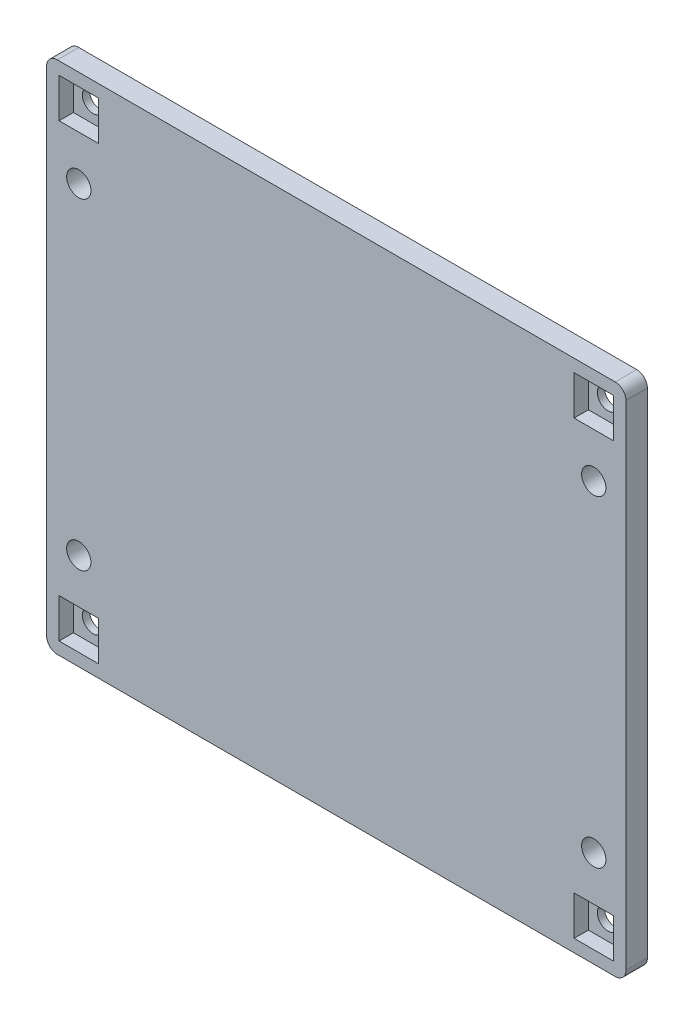
SolidWorks part; units mm, degrees
ref_plane "Alzado" through (0, 0, 0) normal (0, 0, 1) x (1, 0, 0)
ref_plane "Planta" through (0, 0, 0) normal (0, 1, 0) x (1, 0, 0)
ref_plane "Vista lateral" through (0, 0, 0) normal (1, 0, 0) x (0, 0, -1)
sketch "Model" plane through (0, 0, 0) normal (0, 0, 1) x (1, 0, 0)
  line L0 (85.4827, 227.2463) -> (7.4781, 227.2463)
  line L1 (5.9781, 228.7463) -> (5.9781, 297.7487)
  line L2 (7.4781, 299.2487) -> (85.4827, 299.2487)
  line L3 (86.9827, 297.7487) -> (86.9827, 228.7463)
  circle A0 centre (82.483, 294.7487) radius 1.5
  circle A1 centre (10.4781, 231.7459) radius 1.5
  circle A2 centre (82.483, 231.7459) radius 1.5
  circle A3 centre (10.4781, 294.7487) radius 1.5
  circle A4 centre (10.4781, 240.7456) radius 1.7
  circle A5 centre (10.4781, 285.749) radius 1.7
  circle A6 centre (82.483, 240.7456) radius 1.7
  circle A7 centre (82.483, 285.749) radius 1.7
  arc A8 (7.4781, 299.2487) -> (5.9781, 297.7487) centre (7.4781, 297.7487) ccw
  arc A9 (86.9827, 297.7487) -> (85.4827, 299.2487) centre (85.4827, 297.7487) ccw
  arc A10 (85.4827, 227.2463) -> (86.9827, 228.7463) centre (85.4827, 228.7463) ccw
  arc A11 (5.9781, 228.7463) -> (7.4781, 227.2463) centre (7.4781, 228.7463) ccw
extrude "Saliente-Extruir1" add sketch "Model" along normal blind 3
sketch "Croquis2" plane through (0, 0, 3) normal (0, 0, 1) x (1, 0, 0)
  line L1 (7.7281, 297.4987) -> (13.2281, 297.4987)
  line L2 (7.7281, 297.4987) -> (7.7281, 291.9987)
  line L3 (7.7281, 291.9987) -> (13.2281, 291.9987)
  line L4 (13.2281, 297.4987) -> (13.2281, 291.9987)
  line L5 (7.7281, 297.4987) -> (13.2281, 291.9987) construction
  line L6 (7.7281, 291.9987) -> (13.2281, 297.4987) construction
  line L7 (85.233, 297.4987) -> (79.733, 297.4987)
  line L8 (85.233, 297.4987) -> (85.233, 291.9987)
  line L9 (85.233, 291.9987) -> (79.733, 291.9987)
  line L10 (79.733, 297.4987) -> (79.733, 291.9987)
  line L11 (85.233, 297.4987) -> (79.733, 291.9987) construction
  line L12 (85.233, 291.9987) -> (79.733, 297.4987) construction
  line L13 (13.2281, 234.4959) -> (7.7281, 234.4959)
  line L14 (13.2281, 234.4959) -> (13.2281, 228.9959)
  line L15 (13.2281, 228.9959) -> (7.7281, 228.9959)
  line L16 (7.7281, 234.4959) -> (7.7281, 228.9959)
  line L17 (13.2281, 234.4959) -> (7.7281, 228.9959) construction
  line L18 (13.2281, 228.9959) -> (7.7281, 234.4959) construction
  line L19 (79.733, 234.4959) -> (85.233, 234.4959)
  line L20 (79.733, 234.4959) -> (79.733, 228.9959)
  line L21 (79.733, 228.9959) -> (85.233, 228.9959)
  line L22 (85.233, 234.4959) -> (85.233, 228.9959)
  line L23 (79.733, 234.4959) -> (85.233, 228.9959) construction
  line L24 (79.733, 228.9959) -> (85.233, 234.4959) construction
  point P0 (10.4781, 294.7487)
  point P5 (82.483, 294.7487)
  point P12 (10.4781, 231.7459)
  point P18 (82.483, 231.7459)
extrude "Cortar-Extruir1" cut sketch "Croquis2" against normal blind 2
